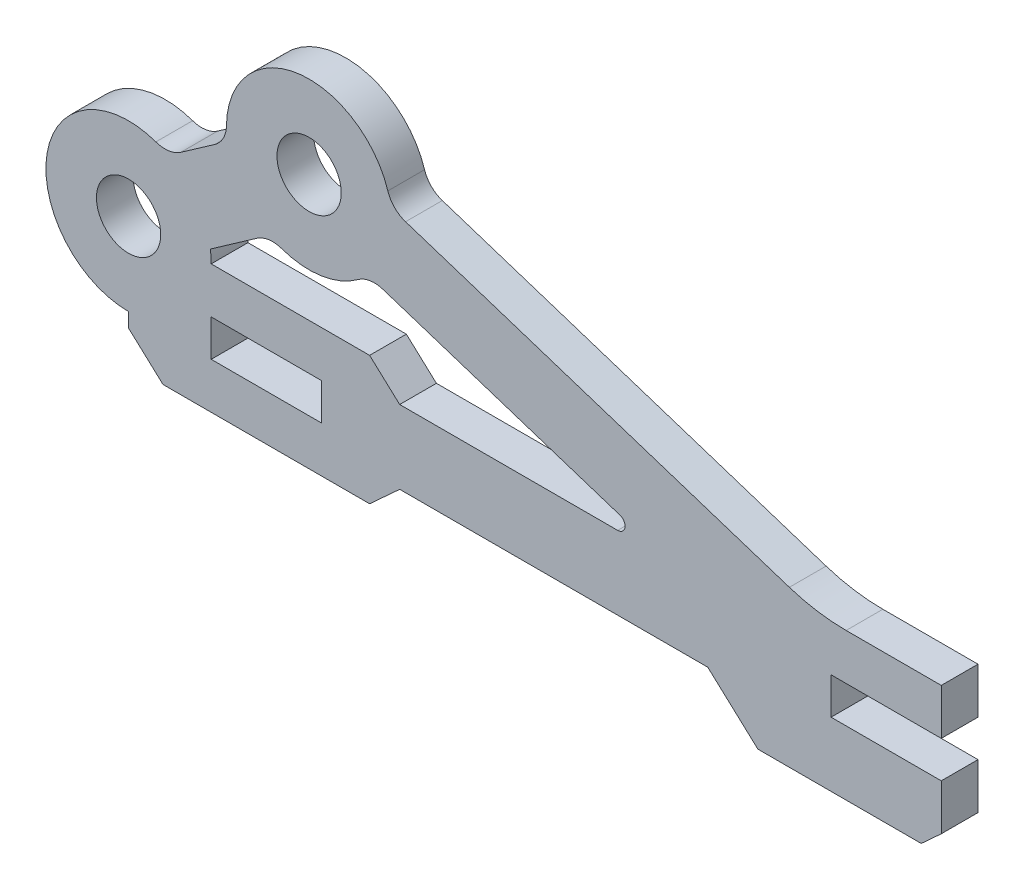
SolidWorks part; units mm, degrees
ref_plane "Front Plane" through (0, 0, 0) normal (0, 0, 1) x (1, 0, 0)
ref_plane "Top Plane" through (0, 0, 0) normal (0, 1, 0) x (1, 0, 0)
ref_plane "Right Plane" through (0, 0, 0) normal (1, 0, 0) x (0, 0, -1)
sketch "Sketch1" plane through (0, 0, 0) normal (0, 0, 1) x (1, 0, 0)
  line L0 (4.6906, 5.726) -> (2.8449, 4.4336)
  line L1 (15.0827, 7.2791) -> (35.9791, 0.4894)
  line L2 (39.0692, 0) -> (44.25, 0)
  line L3 (44.25, 0) -> (44.25, -2.5)
  line L4 (44.25, -2.5) -> (38.25, -2.5)
  line L5 (38.25, -2.5) -> (38.25, -4.5)
  line L6 (38.25, -4.5) -> (44.25, -4.5)
  line L7 (44.25, -4.5) -> (44.25, -8) construction
  line L8 (44.25, -8) -> (34.2647, -8) construction
  line L9 (34.2647, -8) -> (31.5364, -5.5)
  line L10 (31.5364, -5.5) -> (14.762, -5.5)
  line L11 (14.762, -5.5) -> (13.125, -7)
  line L12 (13.125, -7) -> (1.875, -7)
  line L13 (1.875, -7) -> (0, -5.2819)
  line L14 (34.2647, -8) -> (43.1587, -8)
  line L15 (43.1587, -8) -> (44.25, -7)
  line L16 (44.25, -7) -> (44.25, -4.5)
  line L17 (4.5, -4.5) -> (1.875, -7) construction
  line L18 (0, -4.5) -> (2.8449, -4.5) construction
  line L40 (0, -5.2819) -> (0, -4.5)
  line L41 (9.8298, 6.8829) -> (0, 0) construction
  line L42 (0, 0) -> (1.75, 0) construction
  line L43 (9.8298, 6.8829) -> (30.769, 0.0794) construction
  line L44 (4.5, -2.5) -> (10.5, -2.5)
  line L45 (4.5, -2.5) -> (4.5, -4.5)
  line L46 (4.5, -4.5) -> (10.5, -4.5)
  line L47 (10.5, -2.5) -> (10.5, -4.5)
  line L49 (10.5, -4.5) -> (13.125, -7) construction
  line L50 (13.8467, 3.4748) -> (26.7558, -0.7196)
  line L51 (26.6322, -1.5) -> (14.762, -1.5)
  line L52 (14.762, -1.5) -> (13.125, 0)
  line L53 (13.125, 0) -> (4.5, 0)
  line L54 (4.4493, 0.6739) -> (6.9849, 2.4493)
  line L55 (14.762, -1.5) -> (14.762, -5.5) construction
  line L56 (31.5364, -5.5) -> (27.9242, -5.5) construction
  line L57 (13.125, 0) -> (13.125, -7) construction
  line L58 (10.5, -2.5) -> (13.125, 0) construction
  line L59 (9.8298, 6.8829) -> (23.5215, 6.8829) construction
  line L60 (10.5, -3.5) -> (38.25, -3.5) construction
  arc A0 (35.9791, 0.4894) -> (39.0692, 0) centre (39.0692, 10) ccw
  circle A14 centre (0, 0) radius 1.75
  arc A15 (4.5, 0) -> (4.4493, 0.6739) centre (0, 0) ccw
  circle A16 centre (9.8298, 6.8829) radius 1.75
  arc A17 (14.1172, 8.25) -> (5.3301, 6.9367) centre (9.8298, 6.8829) ccw
  arc A18 (1.4884, 4.2467) -> (0, -4.5) centre (0, 0) ccw
  arc A19 (8.3414, 2.6362) -> (12.4948, 3.2569) centre (9.8298, 6.8829) ccw
  arc A20 (26.7558, -0.7196) -> (26.6322, -1.5) centre (26.6322, -1.1) cw
  arc A21 (6.9849, 2.4493) -> (8.3414, 2.6362) centre (7.8453, 1.2206) cw
  arc A22 (13.8467, 3.4748) -> (12.4948, 3.2569) centre (13.3831, 2.0483) ccw
  arc A23 (15.0827, 7.2791) -> (14.1172, 8.25) centre (15.5463, 8.7057) cw
  arc A24 (2.8449, 4.4336) -> (1.4884, 4.2467) centre (1.9845, 5.6623) cw
  arc A25 (4.6906, 5.726) -> (5.3301, 6.9367) centre (3.8303, 6.9547) ccw
  point P93 (7.6749, 2.9325)
  point P100 (2.155, 3.9505)
  dimension "D3" = 3.5
  dimension "D4" = 9
  dimension "D5" = 9
  dimension "D6" = 3.5
  dimension "D29" = 0.4
  dimension "D31" = 1.5
  dimension "D32" = 1.5
  dimension "D28" = 10
  dimension "D7" = 35
  dimension "D8" = 12
  dimension "D9" = 6
  dimension "D10" = 2
  dimension "D11" = 2.5
  dimension "D12" = 27.75
  dimension "D13" = 2
  dimension "D14" = 42.5
  dimension "D15" = 6
  dimension "D16" = 2
  dimension "D17" = 4.5
  dimension "D18" = 2.5
  dimension "D19" = 4
  dimension "D20" = 2
  dimension "D21" = 4
  dimension "D22" = 42.5
  dimension "D23" = 42.5
  dimension "D24" = 42.5
  dimension "D25" = 3.5
  dimension "D26" = 18
  dimension "D27" = 2
  dimension "D30" = 2.5
extrude "Boss-Extrude1" add sketch "Sketch1" along normal blind 2
